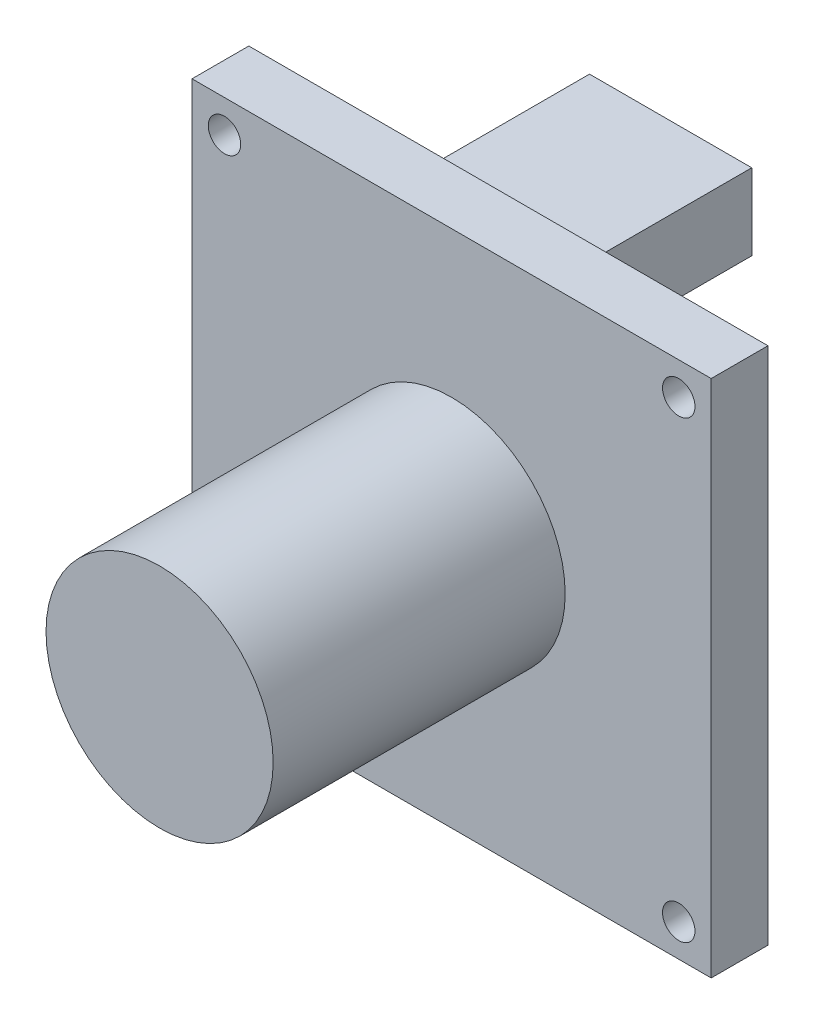
SolidWorks part; units mm, degrees
material "Custom Plastic"
ref_plane "Front Plane" through (0, 0, 0) normal (0, 0, 1) x (1, 0, 0)
ref_plane "Top Plane" through (0, 0, 0) normal (0, 1, 0) x (1, 0, 0)
ref_plane "Right Plane" through (0, 0, 0) normal (1, 0, 0) x (0, 0, -1)
sketch "Sketch1" plane through (0, 0, 0) normal (0, 0, 1) x (1, 0, 0)
  line L1 (-16, -16) -> (16, -16)
  line L2 (-16, -16) -> (-16, 16)
  line L3 (-16, 16) -> (16, 16)
  line L4 (16, -16) -> (16, 16)
  line L5 (-16, -16) -> (16, 16) construction
  line L6 (-16, 16) -> (16, -16) construction
  point P0 (0, 0)
extrude "Boss-Extrude1" add sketch "Sketch1" along normal blind 3.5
sketch "Sketch2" plane through (0, 0, 0) normal (0, 0, 1) x (1, 0, 0)
  circle A0 centre (0, 0) radius 7
extrude "Boss-Extrude2" add sketch "Sketch2" along normal blind 18 from surface at 3.5 starting at face at (0, 0, 3.5)
sketch "Sketch3" plane through (0, 0, 0) normal (0, 0, 1) x (1, 0, 0)
  line L0 (-16, 16) -> (-16, 15) construction
  line L1 (-16, 16) -> (-16, -16) construction
  line L2 (-16, 15) -> (-5, 15) construction
  line L4 (-5, 15) -> (5, 15)
  line L5 (-5, 15) -> (-5, 10.3)
  line L6 (-5, 10.3) -> (5, 10.3)
  line L7 (5, 15) -> (5, 10.3)
extrude "Boss-Extrude3" add sketch "Sketch3" against normal blind 10 from surface at 0 starting at face at (0, 0, 0)
sketch "Sketch4" plane through (0, 0, 0) normal (0, 0, 1) x (1, 0, 0)
  circle A0 centre (14, 14) radius 1
  circle A1 centre (-14, 14) radius 1
  circle A2 centre (-14, -14) radius 1
  circle A3 centre (14, -14) radius 1
  point P0 (0, 0)
extrude "Cut-Extrude1" cut sketch "Sketch4" along normal blind 10
